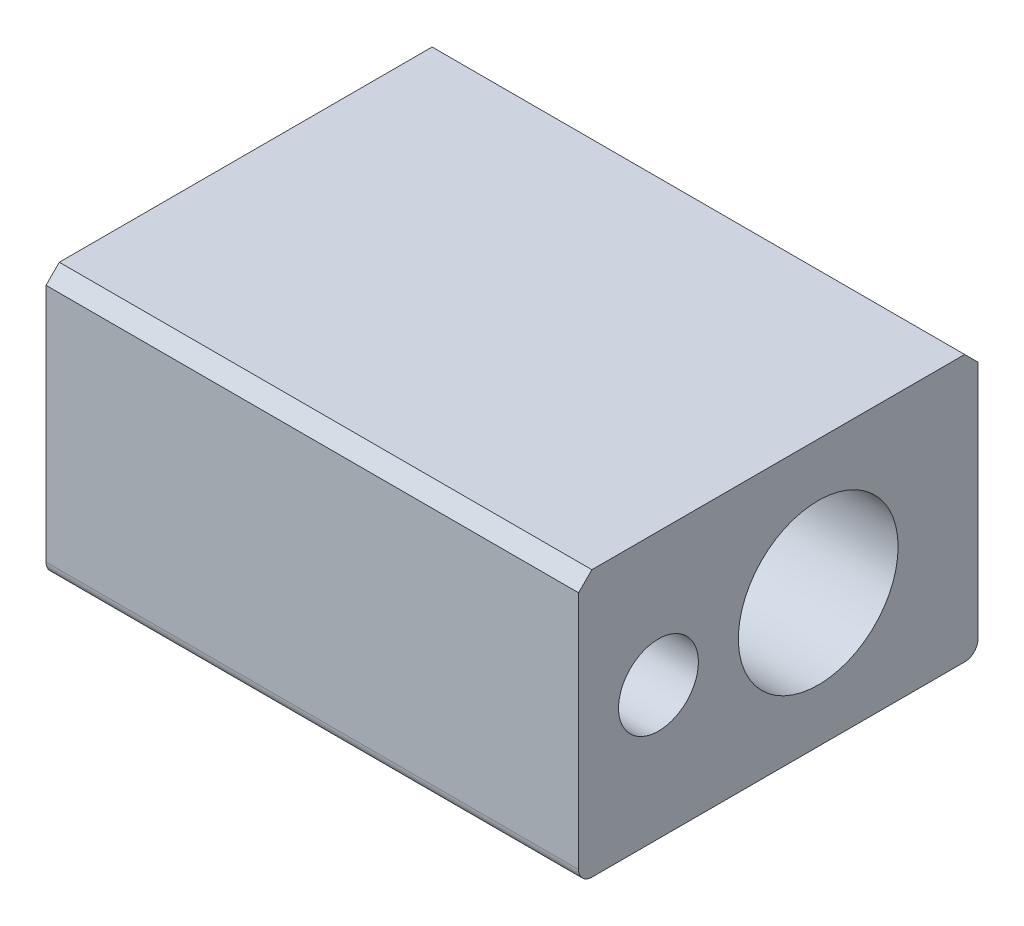
SolidWorks part; units mm, degrees
ref_plane "Front Plane" through (0, 0, 0) normal (1, 0, 0) x (0, 1, 0)
ref_plane "Top Plane" through (0, 0, 0) normal (0, 0, 1) x (0, 1, 0)
ref_plane "Right Plane" through (0, 0, 0) normal (0, 1, 0) x (-1, 0, 0)
sketch "Sketch1" plane through (0, 0, 0) normal (1, 0, 0) x (0, 1, 0)
  line L0 (0, -41.91) -> (0, 41.91) construction
  line L1 (25.4, -38.1) -> (-25.4, -38.1)
  line L2 (25.4, -38.1) -> (25.4, 38.1)
  line L3 (25.4, 38.1) -> (-25.4, 38.1)
  line L4 (-25.4, -38.1) -> (-25.4, 38.1)
  line L5 (25.4, -38.1) -> (-25.4, 38.1) construction
  line L6 (25.4, 38.1) -> (-25.4, -38.1) construction
  circle A0 centre (0, -7.62) radius 15.24
  circle A1 centre (0, 22.86) radius 7.62
  point P0 (0, 0)
  dimension "D3" = 30.48
  dimension "D5" = 15.24
  dimension "D1" = 50.8
  dimension "D2" = 76.2
  dimension "D4" = 30.48
  dimension "D6" = 15.24
extrude "Boss-Extrude1" add sketch "Sketch1" along normal blind 101.6
fillet "Fillet1" radius 2.54 2 edges at (50.8, -25.4, -38.1) (50.8, -25.4, 38.1)
chamfer "Chamfer1" distance 2.54 angle 45 2 edges at (50.8, 25.4, -38.1) (50.8, 25.4, 38.1)
